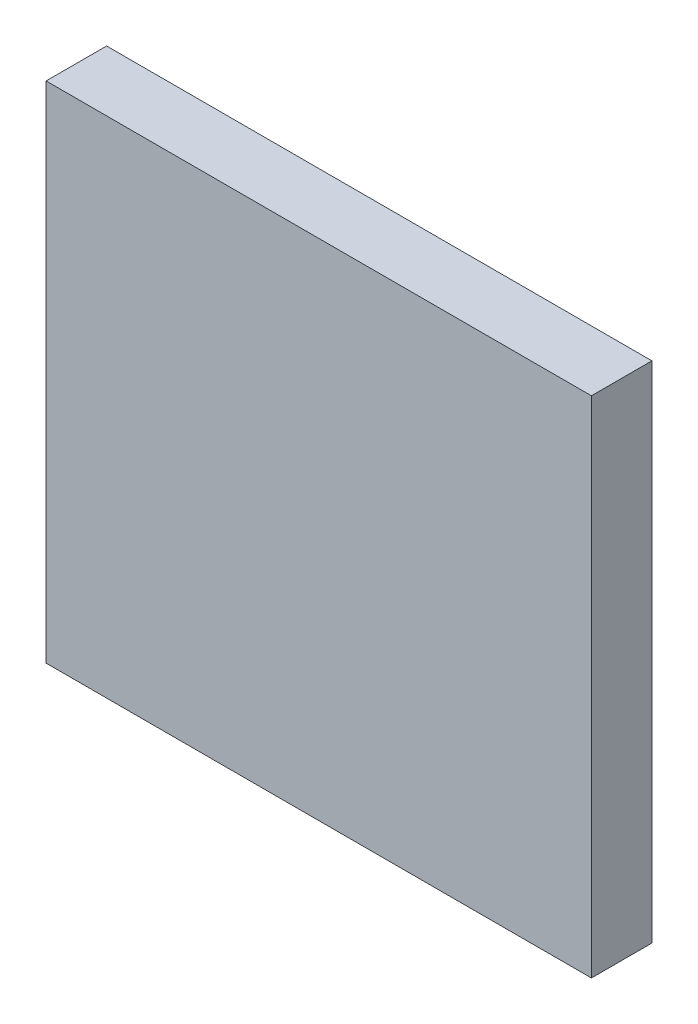
SolidWorks part; units mm, degrees
ref_plane "Front Plane" through (0, 0, 0) normal (0, 0, 1) x (1, 0, 0)
ref_plane "Top Plane" through (0, 0, 0) normal (0, 1, 0) x (1, 0, 0)
ref_plane "Right Plane" through (0, 0, 0) normal (1, 0, 0) x (0, 0, -1)
sketch "Sketch1" plane through (0, 0, 0) normal (0, 0, 1) x (1, 0, 0)
  line L1 (-45.0599, -41.6654) -> (45.0599, -41.6654)
  line L2 (-45.0599, -41.6654) -> (-45.0599, 41.6654)
  line L3 (-45.0599, 41.6654) -> (45.0599, 41.6654)
  line L4 (45.0599, -41.6654) -> (45.0599, 41.6654)
  line L5 (-45.0599, -41.6654) -> (45.0599, 41.6654) construction
  line L6 (-45.0599, 41.6654) -> (45.0599, -41.6654) construction
  point P0 (0, 0)
extrude "Boss-Extrude1" add sketch "Sketch1" along normal blind 10
